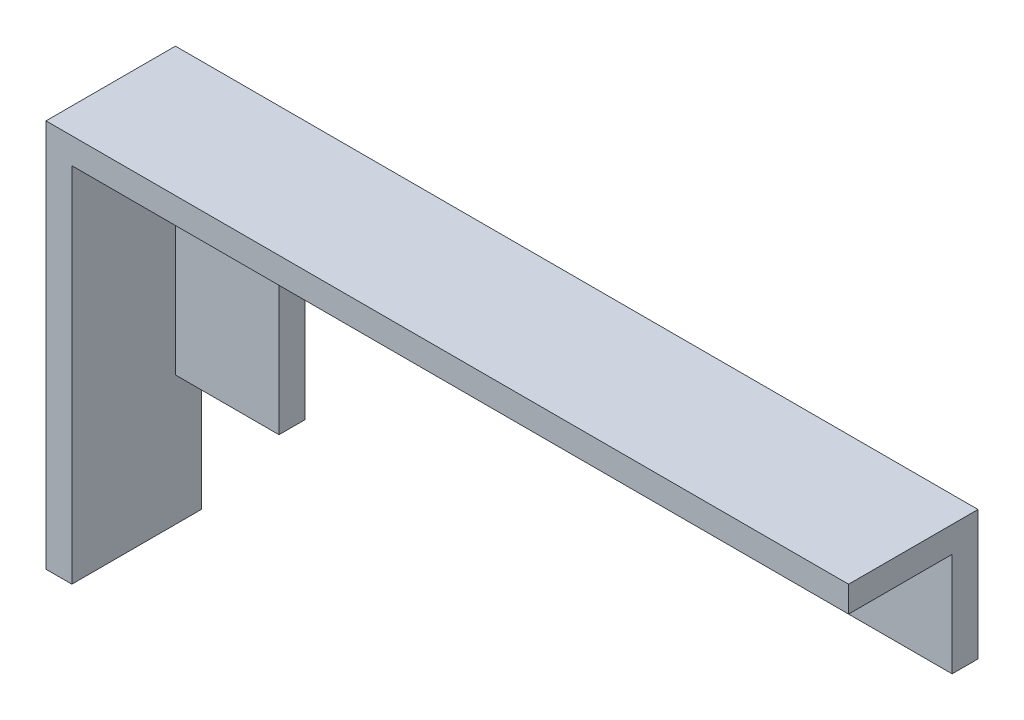
SolidWorks part; units mm, degrees
ref_plane "Plan de face" through (0, 0, 0) normal (0, 0, 1) x (1, 0, 0)
ref_plane "Plan de dessus" through (0, 0, 0) normal (0, 1, 0) x (1, 0, 0)
ref_plane "Plan de droite" through (0, 0, 0) normal (1, 0, 0) x (0, 0, -1)
sketch "Esquisse1" plane through (0, 0, 0) normal (0, 0, 1) x (1, 0, 0)
  line L0 (0, 0) -> (31, 0)
  line L1 (31, 0) -> (31, -5)
  line L2 (31, -5) -> (5, -5)
  line L3 (0, 0) -> (0, -15)
  line L4 (0, -15) -> (1, -15)
  line L5 (1, -15) -> (1, -10)
  line L6 (1, -10) -> (5, -10)
  line L7 (5, -10) -> (5, -5)
  dimension "D1" = 31
  dimension "D2" = 15
  dimension "D3" = 5
  dimension "D4" = 1
  dimension "D5" = 4
  dimension "D6" = 5
extrude "Boss.-Extru.1" add sketch "Esquisse1" along normal blind 5
sketch "Esquisse2" plane through (0, 0, 5) normal (0, 0, 1) x (1, 0, 0)
  line L0 (1, -10) -> (1, -1)
  line L1 (1, -1) -> (31, -1)
  line L2 (31, -5) -> (31, 0) construction
  line L3 (31, -1) -> (31, -5)
  line L4 (31, -5) -> (5, -5)
  line L5 (5, -5) -> (5, -10)
  line L6 (5, -10) -> (1, -10)
  dimension "D1" = 1
extrude "Enlèv. mat.-Extru.1" cut sketch "Esquisse2" against normal blind 4
